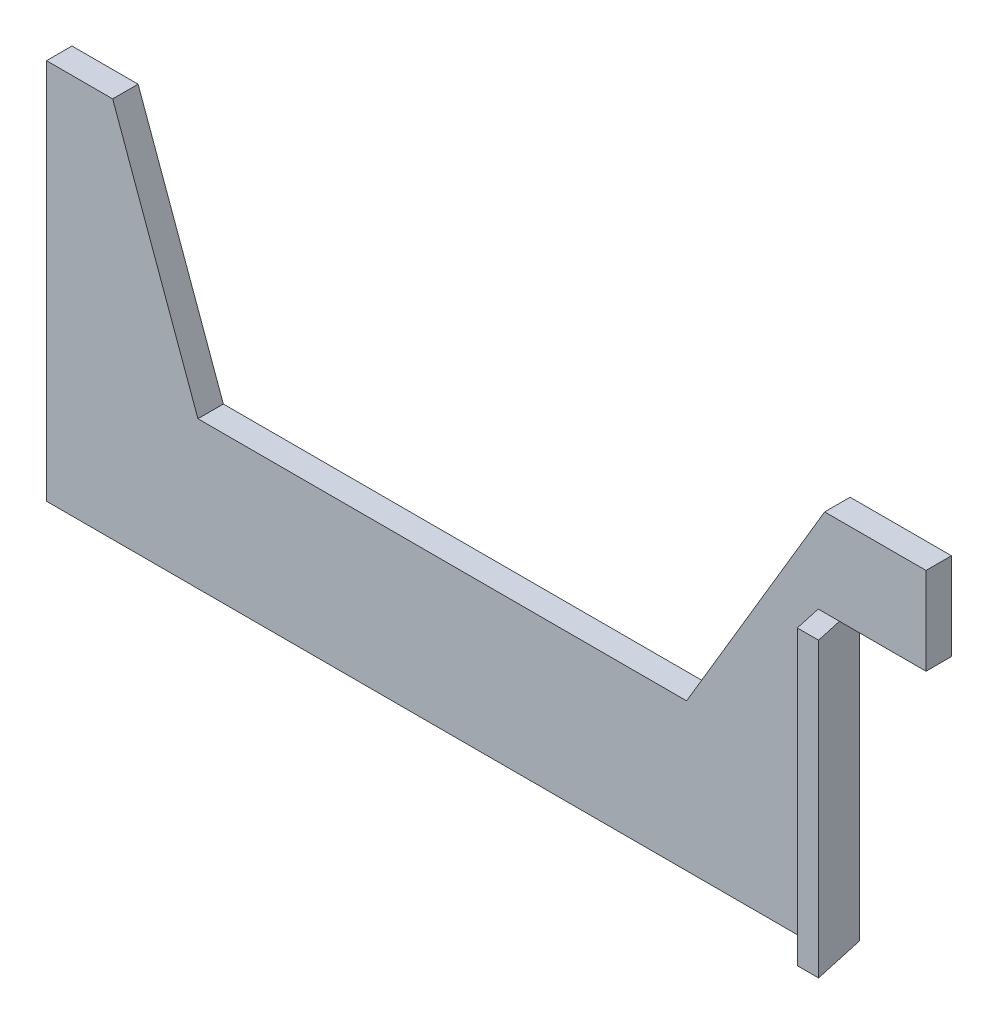
SolidWorks part; units mm, degrees
ref_plane "Front Plane" through (0, 0, 0) normal (0, 0, 1) x (1, 0, 0)
ref_plane "Top Plane" through (0, 0, 0) normal (0, 1, 0) x (1, 0, 0)
ref_plane "Right Plane" through (0, 0, 0) normal (1, 0, 0) x (0, 0, -1)
sketch "Sketch1" plane through (0, 0, 0) normal (0, 0, 1) x (1, 0, 0)
  line L2 (-60.75, -30) -> (-60.75, 30)
  line L11 (63.0497, 16) -> (77.5497, 16)
  line L18 (63.0497, -30) -> (63.0497, 16)
  line L21 (77.5497, 29.7321) -> (77.5497, 16)
  line L23 (-60.75, 30) -> (-50.3529, 30)
  line L24 (-50.3529, 30) -> (-36.9454, -6.8552)
  line L25 (-36.9454, -6.8552) -> (39.8971, -6.8552)
  line L26 (39.8971, -6.8552) -> (61.6068, 29.7321)
  line L27 (61.6068, 29.7321) -> (77.5497, 29.7321)
  line L29 (-60.75, -30) -> (63.0497, -30)
  point P13 (-60.75, 0)
  dimension "D1" = 138.3
  dimension "D2" = 14.5
  dimension "D3" = 46
  dimension "D4" = 60
extrude "Boss-Extrude1" add sketch "Sketch1" along normal mid plane 4
sketch "Sketch2" plane through (0, -30, 0) normal (0, -1, 0) x (1, 0, 0)
  line L0 (63.0497, 2) -> (63.0497, -2) construction
  line L5 (-60.75, 2) -> (63.0497, 2) construction
  line L15 (-60.75, -2) -> (63.0497, -2) construction
  line L18 (63.0497, -2) -> (64.873, 6.2193)
  line L19 (64.873, 6.2193) -> (61.5304, 6.2193)
  line L20 (61.5304, 6.2193) -> (60.5944, 2)
  line L21 (60.5944, 2) -> (63.0497, -2)
  point P0 (60.5944, 2)
extrude "Boss-Extrude2" add sketch "Sketch2" against normal up to surface (46 mm away) up to face at (70.2997, 16, 0)
equation "\"wall_thick_ness\"=4"
equation "\"D1@Boss-Extrude1\"=\"wall_thick_ness\""
equation "\"back_boost\"=7"
equation "\"D1@Sketch1\"=\"back_boost\"+131.30mm"
equation "\"gate\"=11"
equation "\"D2@Sketch1\"=\"gate\"+3.5"
